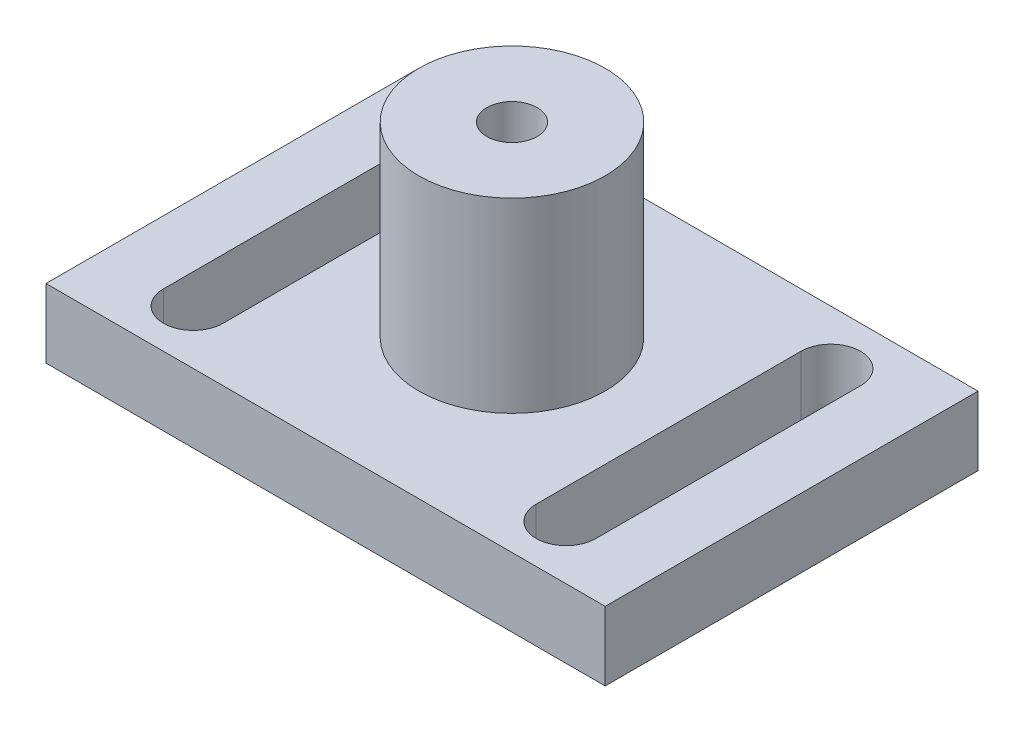
SolidWorks part; units mm, degrees
ref_plane "Front Plane" through (0, 0, 0) normal (0, 0, 1) x (1, 0, 0)
ref_plane "Top Plane" through (0, 0, 0) normal (0, 1, 0) x (1, 0, 0)
ref_plane "Right Plane" through (0, 0, 0) normal (1, 0, 0) x (0, 0, -1)
sketch "Sketch1" plane through (0, 0, 0) normal (0, 1, 0) x (1, 0, 0)
  line L1 (0, 0) -> (76.2, 0)
  line L2 (0, 0) -> (0, 50.8)
  line L3 (0, 50.8) -> (76.2, 50.8)
  line L4 (76.2, 0) -> (76.2, 50.8)
extrude "Boss-Extrude1" add sketch "Sketch1" along normal blind 9.398 contours L2 L1 L4 L3
sketch "Sketch3" plane through (0, 9.398, 0) normal (0, 1, 0) x (1, 0, 0)
  line L0 (8.636, 43.434) -> (8.636, 7.366)
  line L1 (16.764, 43.434) -> (16.764, 7.366)
  line L2 (0, 0) -> (0, 50.8) construction
  line L3 (0, 50.8) -> (76.2, 50.8) construction
  line L4 (0, 0) -> (76.2, 0) construction
  line L5 (38.1, 50.8) -> (38.1, 0)
  line L6 (67.564, 43.434) -> (67.564, 7.366)
  line L7 (59.436, 43.434) -> (59.436, 7.366)
  arc A2 (8.636, 43.434) -> (16.764, 43.434) centre (12.7, 43.434) cw
  arc A3 (8.636, 7.366) -> (16.764, 7.366) centre (12.7, 7.366) ccw
  arc A4 (67.564, 7.366) -> (59.436, 7.366) centre (63.5, 7.366) cw
  arc A5 (67.564, 43.434) -> (59.436, 43.434) centre (63.5, 43.434) ccw
  dimension "D1" = 12.7
  dimension "D3" = 7.366
  dimension "D5" = 4.064
  dimension "D6" = 4.064
  dimension "D2" = 7.366
  dimension "D4" = 12.7
extrude "Cut-Extrude1" cut sketch "Sketch3" against normal blind 9.398 contours L1 A3 L0 A2 | A4 L7 A5 L6
sketch "Sketch4" plane through (0, 9.398, 0) normal (0, 1, 0) x (1, 0, 0)
  line L0 (38.1, 50.8) -> (38.1, 0) construction
  line L2 (0, 0) -> (76.2, 0) construction
  line L3 (0, 25.4) -> (76.2, 25.4) construction
  line L5 (76.2, 0) -> (76.2, 50.8) construction
  line L6 (0, 0) -> (0, 50.8) construction
  line L7 (0, 50.8) -> (76.2, 50.8) construction
  circle A0 centre (38.1, 25.4) radius 12.7
  circle A1 centre (38.1, 25.4) radius 3.429
  point P0 (38.1, 25.4)
  point P3 (38.1, 25.4)
  point P8 (38.1, 25.4)
  point P9 (0, 25.4)
  point P17 (38.1, 50.8)
  point P20 (0, 0)
  dimension "D1" = 25.4
  dimension "D2" = 6.858
extrude "Boss-Extrude2" add sketch "Sketch4" along normal blind 25.4
